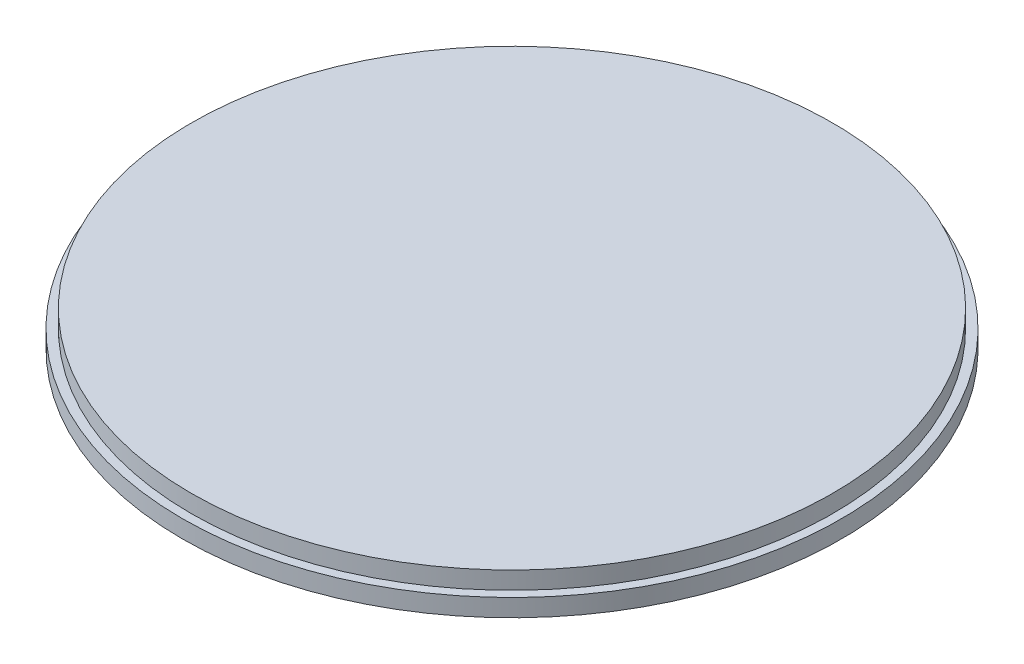
SolidWorks part; units mm, degrees
ref_plane "Front Plane" through (0, 0, 0) normal (0, 0, 1) x (1, 0, 0)
ref_plane "Top Plane" through (0, 0, 0) normal (0, 1, 0) x (1, 0, 0)
ref_plane "Right Plane" through (0, 0, 0) normal (1, 0, 0) x (0, 0, -1)
sketch "Sketch1" plane through (0, 0, 0) normal (0, 1, 0) x (1, 0, 0)
  circle A0 centre (0, 0) radius 18.75
  dimension "D1" = 37.5
extrude "Boss-Extrude1" add sketch "Sketch1" along normal blind 2
sketch "Sketch2" plane through (0, 2, 0) normal (0, 1, 0) x (1, 0, 0)
  circle A0 centre (0, 0) radius 18.25
  dimension "D1" = 36.5
extrude "Cut-Extrude1" cut sketch "Sketch2" against normal blind 1 flip side to cut
